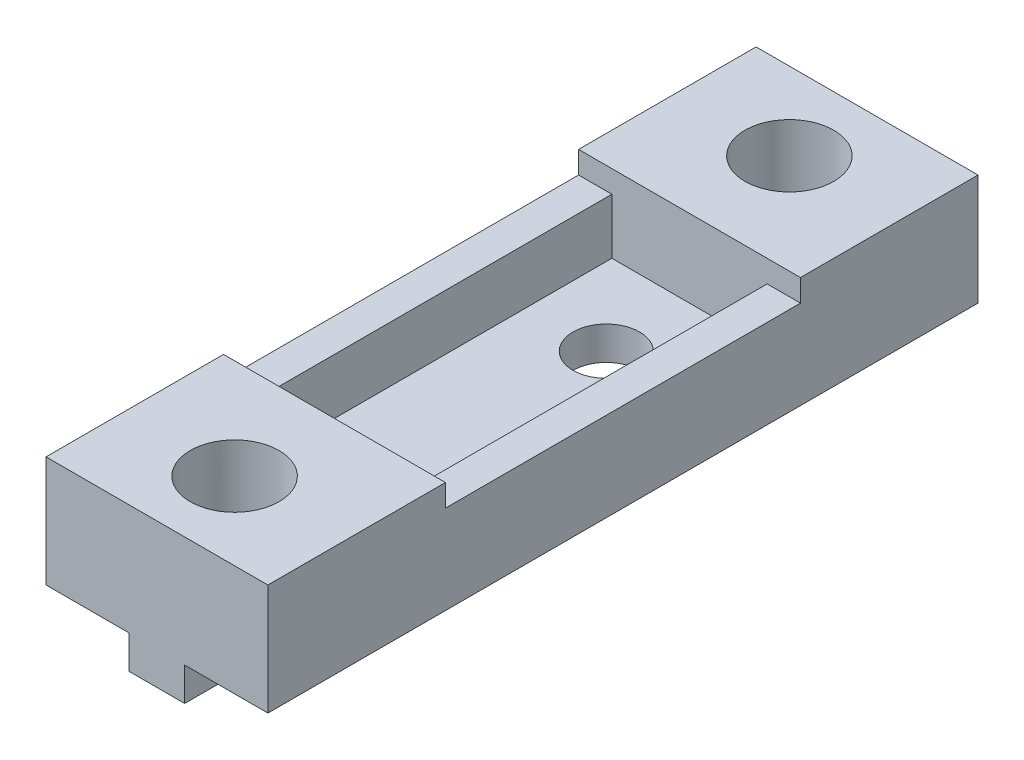
SolidWorks part; units mm, degrees
ref_plane "Front Plane" through (0, 0, 0) normal (0, 0, 1) x (1, 0, 0)
ref_plane "Top Plane" through (0, 0, 0) normal (0, 1, 0) x (1, 0, 0)
ref_plane "Right Plane" through (0, 0, 0) normal (1, 0, 0) x (0, 0, -1)
sketch "Sketch1" plane through (0, 0, 0) normal (0, 1, 0) x (1, 0, 0)
  line L1 (-10, -15) -> (10, -15)
  line L2 (-10, -15) -> (-10, 15)
  line L3 (-10, 15) -> (10, 15)
  line L4 (10, -15) -> (10, 15)
  line L5 (-10, -15) -> (10, 15) construction
  line L6 (-10, 15) -> (10, -15) construction
  point P0 (0, 0)
  dimension "D1" = 20
  dimension "D2" = 30
extrude "Boss-Extrude1" add sketch "Sketch1" along normal blind 3
sketch "Sketch2" plane through (0, 0, 0) normal (0, -1, 0) x (1, 0, 0)
  line L0 (10, -15) -> (-10, -15) construction
  line L1 (-2.5, -15) -> (2.5, -15)
  line L2 (-2.5, -15) -> (-2.5, -3)
  line L3 (-2.5, -3) -> (2.5, -3)
  line L4 (2.5, -15) -> (2.5, -3)
  line L5 (-2.5, -15) -> (2.5, -3) construction
  line L6 (-2.5, -3) -> (2.5, -15) construction
  point P0 (0, -9)
  dimension "D1" = 0
  dimension "D2" = 5
  dimension "D3" = 0
  dimension "D4" = 12
extrude "Boss-Extrude2" add sketch "Sketch2" along normal blind 3
sketch "Sketch3" plane through (0, 3, 0) normal (0, 1, 0) x (1, 0, 0)
  line L0 (10, 15) -> (-10, 15) construction
  circle A0 centre (0, 8) radius 4
  circle A1 centre (0, 8) radius 7
  dimension "D1" = 14
  dimension "D2" = 7
  dimension "D3" = 8
extrude "Boss-Extrude3" add sketch "Sketch3" along normal blind 7
sketch "Sketch4" plane through (0, 3, 0) normal (0, 1, 0) x (1, 0, 0)
  circle A1 centre (0, 8) radius 4
  circle A2 centre (0, 8) radius 4
  dimension "D1" = 0
extrude "Boss-Extrude4" add sketch "Sketch4" along normal blind 1
sketch "Sketch5" plane through (0, 3, 0) normal (0, 1, 0) x (1, 0, 0)
  line L0 (-10, -15) -> (10, -15) construction
  circle A0 centre (0, -8.5) radius 3
  dimension "D1" = 6
  dimension "D2" = 6.5
  dimension "D3" = 0
extrude "Cut-Extrude1" cut sketch "Sketch5" against normal through all both and the other way through all
chamfer "Chamfer1" [suppressed] distance 4 angle 45
sketch "Sketch6" plane through (0, 3, 0) normal (0, 1, 0) x (1, 0, 0)
  line L0 (10, -15) -> (10, 15) construction
  line L1 (-10, 15) -> (10, 15)
  line L2 (-10, 15) -> (-10, -1)
  line L3 (-10, -1) -> (10, -1)
  line L4 (10, 15) -> (10, -1)
  circle A0 centre (0, 8) radius 7 construction
  circle A1 centre (0, 8) radius 7
  circle A3 centre (0, 8) radius 4
  circle A4 centre (0, 8) radius 4
  line M6 (10, 15) -> (0, 15)
  circle M7 centre (0, 8) radius 7
  line M8 (0, 15) -> (-10, 15)
  line M9 (-10, 15) -> (-10, -15)
  line M11 (10, -15) -> (10, 15)
  dimension "D1" = 16
  dimension "D2" = 0
extrude "Boss-Extrude6" add sketch "Sketch6" along normal up to surface (7 mm away) contours A4 M7 | L3 M9 M11 M6 M7 M8 up to face at (0, 10, -1)
ref_plane "Plane1" through (0, 0, -8) normal (0, 0, 1) x (1, 0, 0)
ref_plane "Plane2" through (0, 0, 17) normal (0, 0, 1) x (1, 0, 0)
sketch "Sketch7" plane through (0, 0, 15) normal (0, 0, 1) x (1, 0, 0)
  line L4 (-10, 0) -> (10, 0)
  line L5 (10, 0) -> (10, 3)
  line L6 (10, 3) -> (-10, 3)
  line L7 (-10, 3) -> (-10, 0)
  line L8 (-10, 0) -> (10, 0)
  line L9 (10, 0) -> (10, 3)
  line L10 (10, 3) -> (-10, 3)
  line L11 (-10, 3) -> (-10, 0)
  dimension "D1" = 0
extrude "Boss-Extrude7" add sketch "Sketch7" along normal blind 19
mirror "Mirror3" about plane through (0, 0, 17) normal (0, 0, 1) of "Boss-Extrude6", "Boss-Extrude4", "Boss-Extrude3", "Boss-Extrude2", "Boss-Extrude1"
sketch "Sketch8" plane through (0, 0, 37) normal (0, 0, -1) x (-1, 0, 0)
  line L4 (2.5, 0) -> (-2.5, 0)
  line L5 (-2.5, 0) -> (-2.5, -3)
  line L6 (-2.5, -3) -> (2.5, -3)
  line L7 (2.5, -3) -> (2.5, 0)
  line L8 (2.5, 0) -> (-2.5, 0)
  line L9 (-2.5, 0) -> (-2.5, -3)
  line L10 (-2.5, -3) -> (2.5, -3)
  line L11 (2.5, -3) -> (2.5, 0)
  dimension "D1" = 0
extrude "Boss-Extrude8" add sketch "Sketch8" along normal blind 12
sketch "Sketch10" plane through (0, 4, 0) normal (0, 1, 0) x (1, 0, 0)
  circle A0 centre (0, 8) radius 4 construction
  circle A1 centre (0, -42) radius 4 construction
  circle A2 centre (0, 8) radius 4
  circle A3 centre (0, -42) radius 4
extrude "Cut-Extrude2" cut sketch "Sketch10" against normal blind 1.5
sketch "Sketch12" plane through (0, 3, 0) normal (0, 1, 0) x (1, 0, 0)
  line L1 (10, -33) -> (7, -33)
  line L2 (10, -33) -> (10, -1)
  line L3 (10, -1) -> (7, -1)
  line L4 (-10, -1) -> (-10, -33)
  line L5 (-10, -33) -> (10, -33)
  line L6 (10, -33) -> (10, -1)
  line L7 (10, -1) -> (-10, -1)
  line L8 (-10, -1) -> (-10, -33)
  line L9 (-10, -33) -> (10, -33)
  line L10 (10, -33) -> (10, -1)
  line L11 (10, -1) -> (-10, -1)
  line L12 (7, -33) -> (7, -1)
  line L13 (-10, -33) -> (-7, -33)
  line L14 (-10, -33) -> (-10, -1)
  line L15 (-10, -1) -> (-7, -1)
  line L16 (-7, -33) -> (-7, -1)
  line M11 (-10, -1) -> (-10, -33)
  line M12 (-10, -33) -> (10, -33)
  line M13 (10, -33) -> (10, -1)
  line M14 (10, -1) -> (-10, -1)
  dimension "D2" = 3
  dimension "D3" = 3
  dimension "D1" = 0
extrude "Boss-Extrude9" add sketch "Sketch12" along normal blind 5 contours L12 M12 M13 M14 | L16 L11 M12 M11
